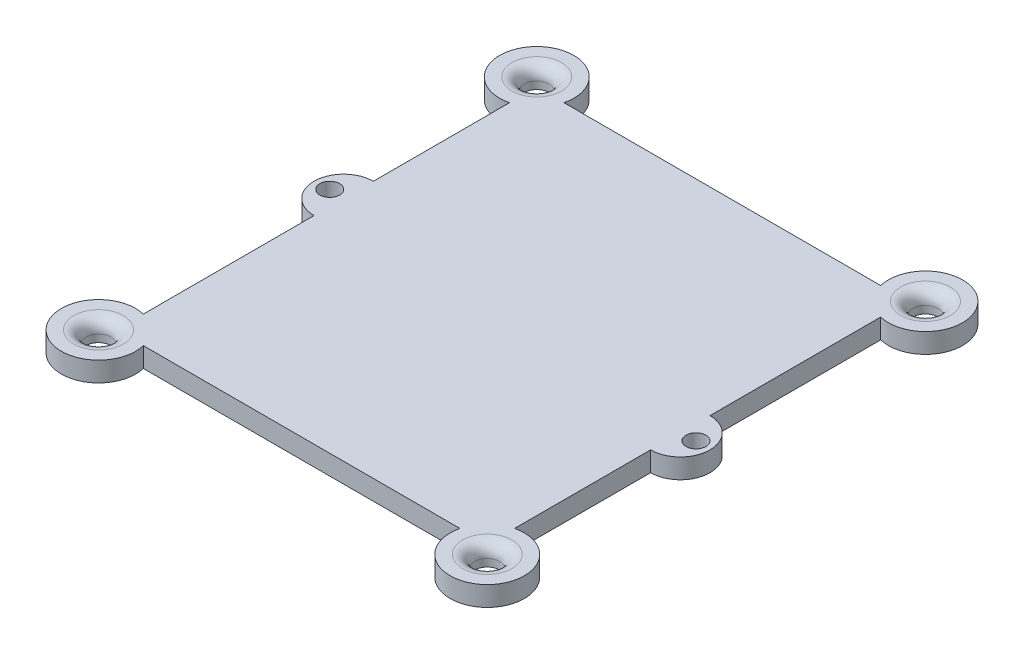
SolidWorks part; units mm, degrees
ref_plane "Front Plane" through (0, 0, 0) normal (0, 0, 1) x (1, 0, 0)
ref_plane "Top Plane" through (0, 0, 0) normal (0, 1, 0) x (1, 0, 0)
ref_plane "Right Plane" through (0, 0, 0) normal (1, 0, 0) x (0, 0, -1)
sketch "Sketch1" plane through (0, 0, 0) normal (0, 1, 0) x (1, 0, 0)
  line L0 (-97.4951, 2.2451) -> (-95.25, 0) construction
  line L1 (-7.0116, 0) -> (-88.2384, 0)
  line L2 (0, -7.0116) -> (0, -100.9384)
  line L3 (-7.0116, -107.95) -> (-88.2384, -107.95)
  line L4 (-95.25, -7.0116) -> (-95.25, -100.9384)
  line L5 (2.2451, 2.2451) -> (0, 0) construction
  line L6 (2.2451, -110.1951) -> (0, -107.95) construction
  line L7 (-97.4951, -110.1951) -> (-95.25, -107.95) construction
  circle A0 centre (-97.4951, 2.2451) radius 3.175
  arc A1 (-88.2384, 0) -> (-95.25, -7.0116) centre (-97.4951, 2.2451) ccw
  circle A2 centre (2.2451, 2.2451) radius 3.175
  arc A3 (0, -7.0116) -> (-7.0116, 0) centre (2.2451, 2.2451) ccw
  circle A4 centre (2.2451, -110.1951) radius 3.175
  arc A5 (-7.0116, -107.95) -> (0, -100.9384) centre (2.2451, -110.1951) ccw
  circle A6 centre (-97.4951, -110.1951) radius 3.175
  arc A7 (-95.25, -100.9384) -> (-88.2384, -107.95) centre (-97.4951, -110.1951) ccw
  dimension "D5" = 6.35
  dimension "D7" = 6.35
  dimension "D3" = 6.35
  dimension "D6" = 6.35
  dimension "D11" = 6.35
  dimension "D12" = 6.35
  dimension "D13" = 6.35
  dimension "D14" = 6.35
  dimension "D1" = 95.25
  dimension "D2" = 107.95
  dimension "D4" = 135
  dimension "D8" = 135
  dimension "D9" = 135
  dimension "D10" = 135
extrude "Boss-Extrude1" add sketch "Sketch1" along normal blind 5.08
sketch "Sketch2" plane through (-95.25, 0, 0) normal (-1, 0, 0) x (0, 0, 1)
  line L0 (7.0116, 5.08) -> (100.9384, 5.08) construction
  line L1 (49.53, 5.08) -> (57.15, 5.08)
  line L2 (49.53, 5.08) -> (49.53, 0)
  line L3 (49.53, 0) -> (57.15, 0)
  line L4 (57.15, 5.08) -> (57.15, 0)
  line L5 (7.0116, 0) -> (100.9384, 0) construction
  dimension "D1" = 7.62
revolve "Revolve1" add sketch "Sketch2" angle 180 about L2
sketch "Sketch3" plane through (0, 0, 0) normal (1, 0, 0) x (0, 0, -1)
  line L0 (-100.9384, 5.08) -> (-7.0116, 5.08) construction
  line L1 (-58.42, 5.08) -> (-66.04, 5.08)
  line L2 (-58.42, 5.08) -> (-58.42, 0)
  line L3 (-58.42, 0) -> (-66.04, 0)
  line L4 (-66.04, 5.08) -> (-66.04, 0)
  line L5 (-100.9384, 0) -> (-7.0116, 0) construction
  point P8 (-58.42, 2.54)
  dimension "D1" = 7.62
revolve "Revolve2" add sketch "Sketch3" angle 180 about L2
sketch "Sketch4" plane through (0, 5.08, 0) normal (0, 1, 0) x (1, 0, 0)
  line L0 (-95.25, -57.15) -> (-95.25, -100.9384) construction
  circle A0 centre (-99.0536, -49.3098) radius 2.54
  arc A1 (-95.25, -41.91) -> (-95.25, -57.15) centre (-95.25, -49.53) ccw construction
  dimension "D1" = 5.08
  dimension "D2" = 3.81
  dimension "D3" = 3.8036
extrude "Cut-Extrude1" cut sketch "Sketch4" against normal through all contours A0
sketch "Sketch5" plane through (0, 5.08, 0) normal (0, 1, 0) x (1, 0, 0)
  line L0 (0, -100.9384) -> (0, -66.04) construction
  circle A0 centre (3.8045, -58.2144) radius 2.54
  arc A1 (0, -66.04) -> (0, -50.8) centre (0, -58.42) ccw construction
  dimension "D1" = 5.08
  dimension "D2" = 3.81
  dimension "D3" = 3.8045
extrude "Cut-Extrude2" cut sketch "Sketch5" against normal through all
fillet "Fillet1" radius 3.175 4 edges at (2.2451, 5.08, 113.3701) (-97.4951, 5.08, 0.9299) (2.2451, 5.08, 0.9299) (-97.4951, 5.08, 113.3701)
